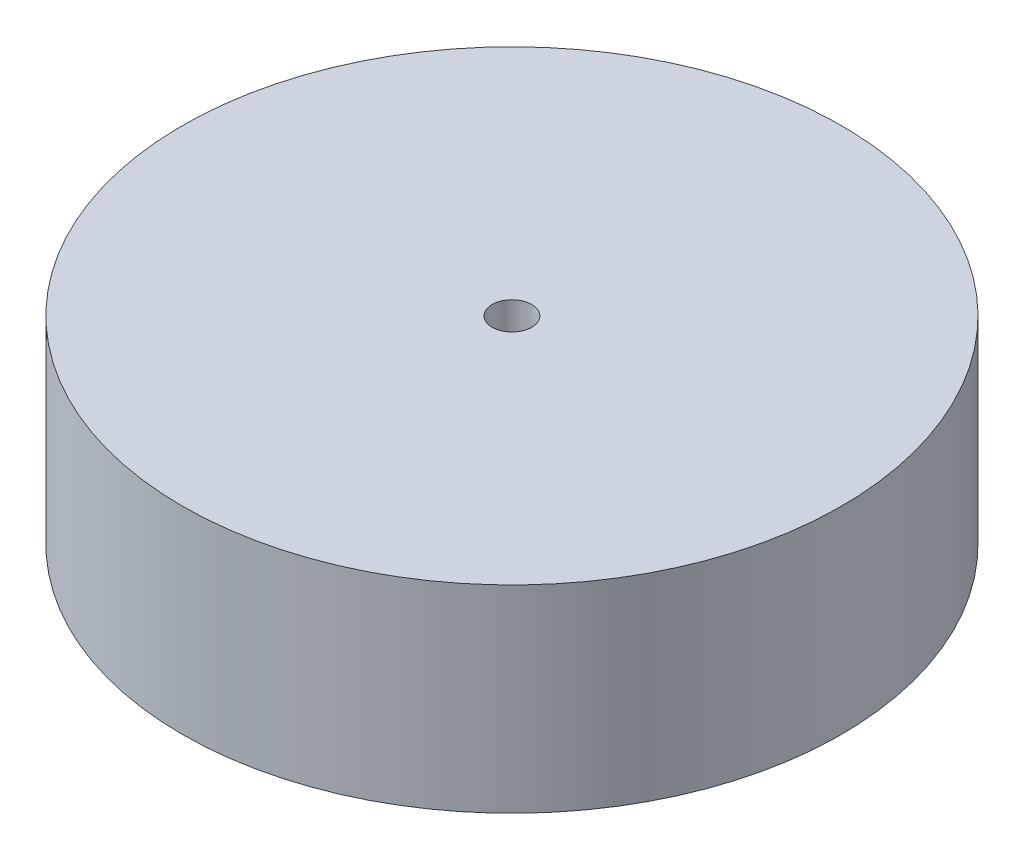
SolidWorks part; units mm, degrees
material "Настроенная пользователем пластмасса"
ref_plane "Спереди" through (0, 0, 0) normal (0, 0, 1) x (1, 0, 0)
ref_plane "Сверху" through (0, 0, 0) normal (0, 1, 0) x (1, 0, 0)
ref_plane "Справа" through (0, 0, 0) normal (1, 0, 0) x (0, 0, -1)
sketch "Эскиз1" plane through (0, 0, 0) normal (0, 1, 0) x (1, 0, 0)
  circle A0 centre (0, 0) radius 50
  circle A1 centre (0, 0) radius 3
  dimension "D1" = 100
  dimension "D2" = 6
extrude "Бобышка-Вытянуть1" add sketch "Эскиз1" along normal blind 30
sketch "Эскиз2" plane through (0, 0, 0) normal (0, 0, 1) x (1, 0, 0)
  line L0 (0, 0) -> (0, 22.7307) construction
  line L1 (-15, 30) -> (-45, 30)
  line L2 (50, 30) -> (-50, 30) construction
  line L3 (-45, 30) -> (-40, 20)
  line L4 (-40, 20) -> (-20, 20)
  line L5 (-20, 20) -> (-15, 30)
  line L6 (-2.5, 50) -> (-2.5, 52.5745) construction
  line L8 (-2.5, 52.5745) -> (0, 52.5745) construction
  dimension "D1" = 45
  dimension "D2" = 15
  dimension "D3" = 2.5
  dimension "D4" = 20
  dimension "D5" = 10
revolve "Вырез-Повернуть1" [suppressed] cut sketch "Эскиз2" angle 360 about L0
